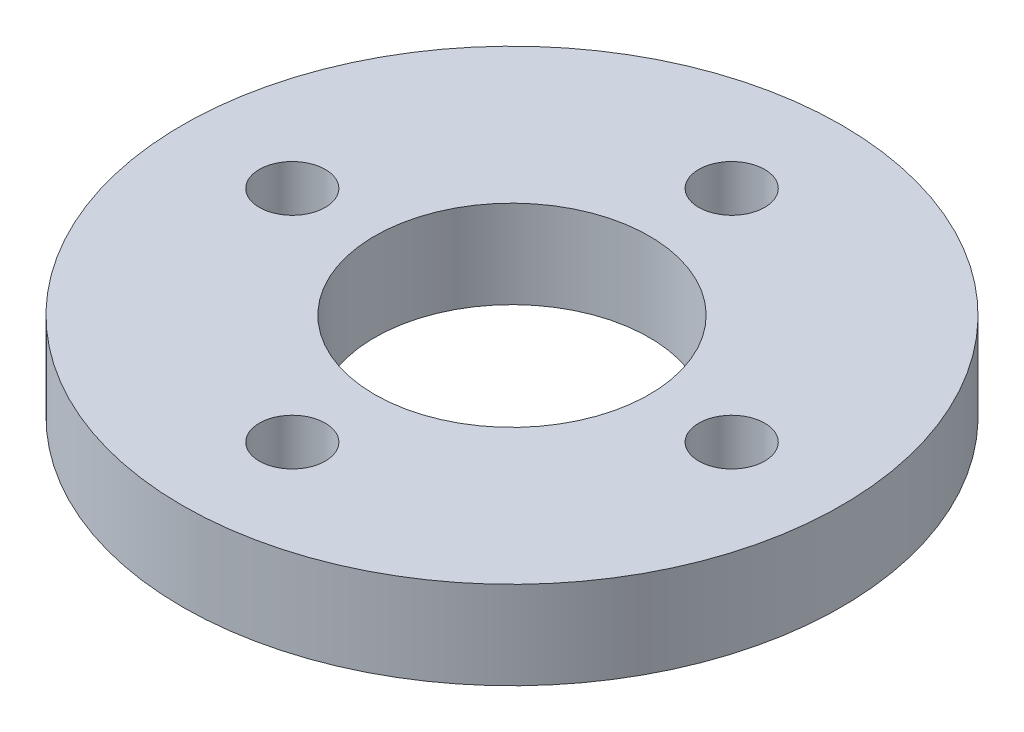
SolidWorks part; units mm, degrees
ref_plane "前视基准面" through (0, 0, 0) normal (0, 0, 1) x (1, 0, 0)
ref_plane "上视基准面" through (0, 0, 0) normal (0, 1, 0) x (1, 0, 0)
ref_plane "右视基准面" through (0, 0, 0) normal (1, 0, 0) x (0, 0, -1)
other "Configuration Table"
sketch "草图1" plane through (0, 0, 0) normal (0, 1, 0) x (1, 0, 0)
  circle A0 centre (0, 0) radius 15
  circle A1 centre (0, 0) radius 6.25
  circle A2 centre (0, 0) radius 10 construction
  circle A3 centre (0, 10) radius 1.5
  circle A4 centre (10, 0) radius 1.5
  circle A5 centre (0, -10) radius 1.5
  circle A6 centre (-10, 0) radius 1.5
  point P16 (0, 0)
  dimension "D1" = 30
  dimension "D2" = 12.5
  dimension "D3" = 20
  dimension "D4" = 3
  dimension "D5" = 4
extrude "凸台-拉伸1" add sketch "草图1" along normal blind 4
